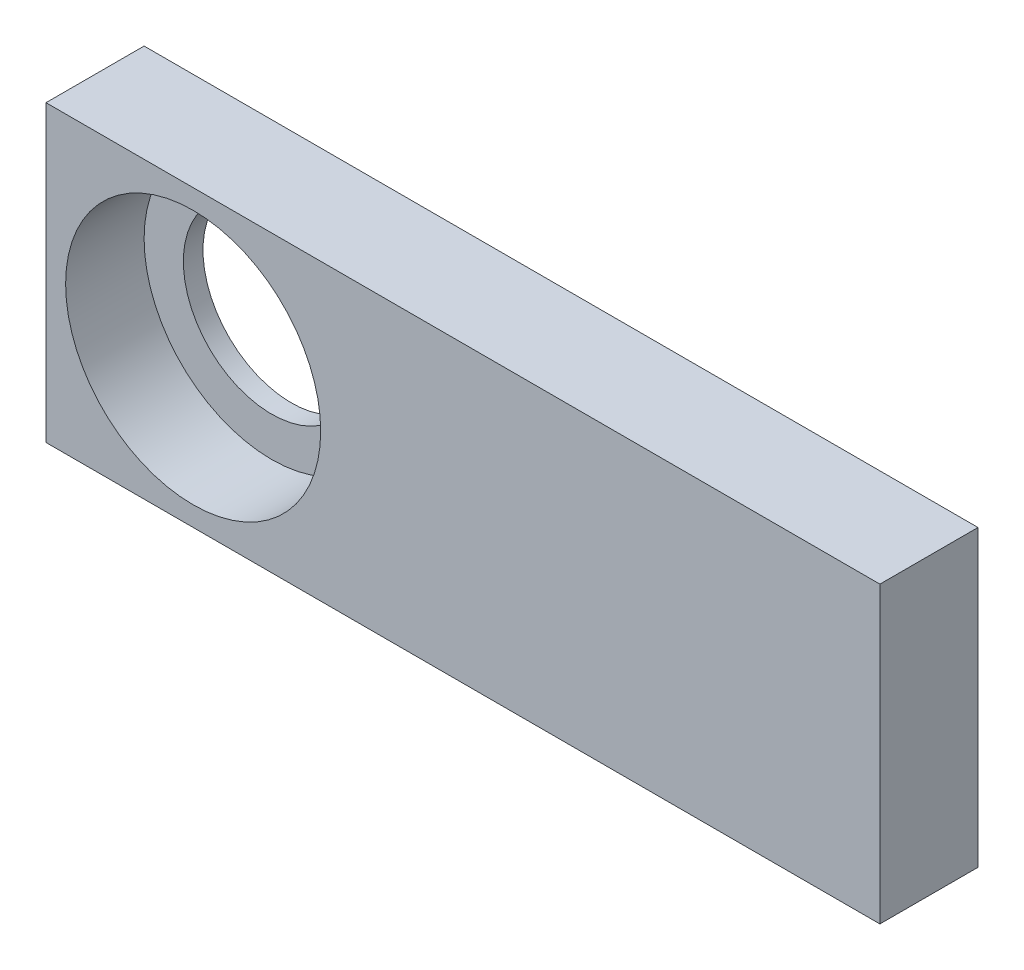
SolidWorks part; units mm, degrees
ref_plane "Plano frontal" through (0, 0, 0) normal (0, 0, 1) x (1, 0, 0)
ref_plane "Plano superior" through (0, 0, 0) normal (0, 1, 0) x (1, 0, 0)
ref_plane "Plano direito" through (0, 0, 0) normal (1, 0, 0) x (0, 0, -1)
sketch "Esboço1" plane through (0, 0, 0) normal (0, 0, 1) x (1, 0, 0)
  line L0 (75, 15) -> (-75, -15) construction
  line L1 (-75, 15) -> (75, 15)
  line L2 (-75, 15) -> (-75, -15)
  line L3 (-75, -15) -> (75, -15)
  line L4 (75, 15) -> (75, -15)
  dimension "D1" = 150
  dimension "D2" = 30
extrude "Ressalto-extrusão1" add sketch "Esboço1" along normal blind 10
sketch "Esboço2" plane through (0, 0, 10) normal (0, 0, 1) x (1, 0, 0)
  line L0 (-45, 15) -> (-45, -15) construction
  line L1 (75, 15) -> (-75, 15) construction
  line L2 (-75, -15) -> (75, -15) construction
  line L3 (-75, 15) -> (-75, -15) construction
  line L4 (-45, 15) -> (-75, -15) construction
  circle A0 centre (-60, 0) radius 13
  dimension "D2" = 26
  dimension "D1" = 30
extrude "Corte-extrusão1" cut sketch "Esboço2" against normal blind 8
sketch "Esboço3" plane through (0, 0, 2) normal (0, 0, 1) x (1, 0, 0)
  circle A0 centre (-60, 0) radius 9
  dimension "D1" = 18
extrude "Corte-extrusão2" cut sketch "Esboço3" against normal up to next
sketch "Esboço4" plane through (0, -15, 0) normal (0, -1, 0) x (1, 0, 0)
  line L0 (-75, 10) -> (75, 10) construction
  line L1 (75, 0) -> (10, 0)
  line L2 (75, 0) -> (75, 10)
  line L3 (75, 10) -> (10, 10)
  line L4 (10, 0) -> (10, 10)
  dimension "D1" = 65
extrude "Corte-extrusão3" cut sketch "Esboço4" against normal up to next
